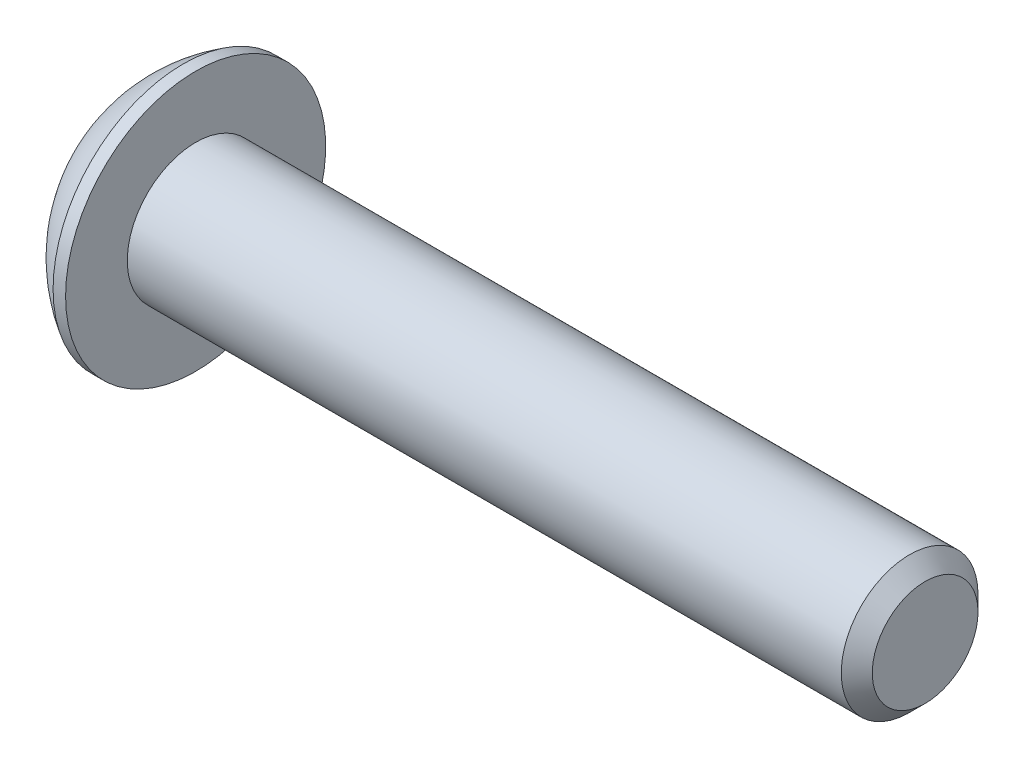
SolidWorks part; units mm, degrees
ref_plane "Front Plane" through (0, 0, 0) normal (0, 0, 1) x (1, 0, 0)
ref_plane "Top Plane" through (0, 0, 0) normal (0, 1, 0) x (1, 0, 0)
ref_plane "Right Plane" through (0, 0, 0) normal (1, 0, 0) x (0, 0, -1)
ref_plane "Plane1" through (0, 0, 0) normal (0, 0, -1) x (-1, 0, 0)
sketch "Sketch1" plane through (0, 0, 0) normal (0, 0, -1) x (-1, 0, 0)
  line L0 (-2.2098, 3.9624) -> (-2.2098, 0)
  line L1 (-2.2098, 0) -> (0, 0)
  line L2 (0, 0) -> (0, 1.9812)
  line L3 (-1.8288, 3.9624) -> (-2.2098, 3.9624)
  line L4 (-2.2098, 0) -> (0, 0) construction
  arc A0 (0, 1.9812) -> (-1.8288, 3.9624) centre (-4.1338, 0) ccw
revolve "Revolve1" add sketch "Sketch1" angle 360 about L4
sketch "Sketch2" plane through (2.2098, 0, 0) normal (1, 0, 0) x (0, 0, -1)
  circle A0 centre (0, 0) radius 2.0828
extrude "Boss-Extrude1" add sketch "Sketch2" along normal blind 22.225
sketch "Sketch3" plane through (0, 0, 0) normal (-1, 0, 0) x (0, 0, 1)
  line L0 (1.1938, 0.6892) -> (0, 1.3785)
  line L1 (0, 1.3785) -> (-1.1938, 0.6892)
  line L2 (-1.1938, 0.6892) -> (-1.1938, -0.6892)
  line L3 (-1.1938, -0.6892) -> (0, -1.3785)
  line L4 (0, -1.3785) -> (1.1938, -0.6892)
  line L5 (1.1938, -0.6892) -> (1.1938, 0.6892)
extrude "Cut-Extrude1" cut sketch "Sketch3" against normal blind 1.3208
sketch "Sketch4" plane through (0, 0, 0) normal (0, 0, 1) x (1, 0, 0)
  line L0 (1.3208, 1.1938) -> (1.3208, 0)
  line L1 (1.3208, 0) -> (2.01, 0)
  line L2 (2.01, 0) -> (1.3208, 1.1938)
  line L3 (1.3208, 0) -> (2.0101, 0) construction
revolve "Cut-Revolve1" cut sketch "Sketch4" angle 360 about L3
chamfer "Chamfer1" distance 0.4724 angle 45 1 edges at (24.4348, 0, -2.0828)
